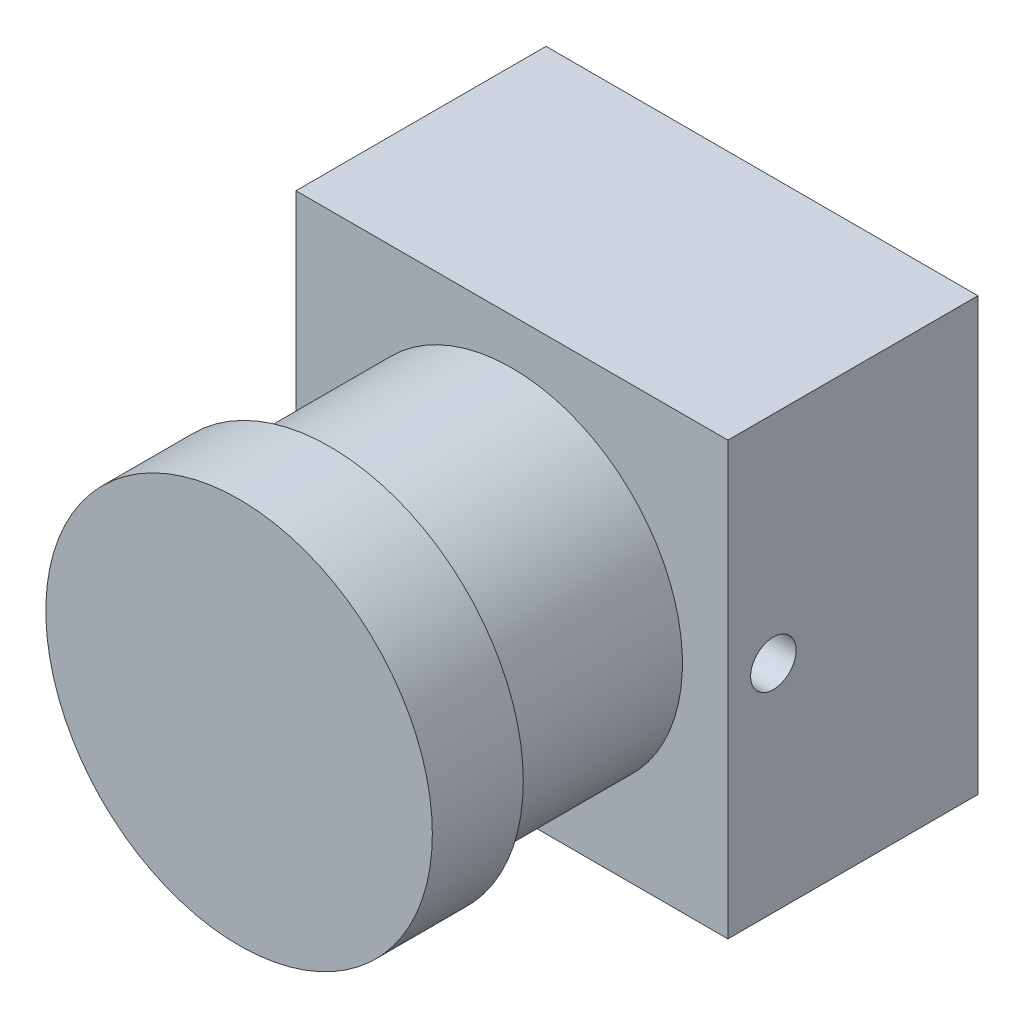
SolidWorks part; units mm, degrees
ref_plane "Front Plane" through (0, 0, 0) normal (0, 0, 1) x (1, 0, 0)
ref_plane "Top Plane" through (0, 0, 0) normal (0, 1, 0) x (1, 0, 0)
ref_plane "Right Plane" through (0, 0, 0) normal (1, 0, 0) x (0, 0, -1)
sketch "Sketch1" plane through (0, 0, 0) normal (0, 0, 1) x (1, 0, 0)
  line L1 (0, 0) -> (19, 0)
  line L2 (0, 0) -> (0, 19)
  line L3 (0, 19) -> (19, 19)
  line L4 (19, 0) -> (19, 19)
  dimension "D1" = 19
extrude "Boss-Extrude1" add sketch "Sketch1" along normal blind 11
sketch "Sketch2" plane through (0, 0, 11) normal (0, 0, 1) x (1, 0, 0)
  line L0 (0, 19) -> (19, 0) construction
  line L1 (19, 19) -> (0, 0) construction
  circle A0 centre (9.5, 9.5) radius 7.5
  point P11 (9.5, 9.5)
  dimension "D1" = 15
extrude "Boss-Extrude2" add sketch "Sketch2" along normal blind 8
sketch "Sketch4" plane through (0, 0, 19) normal (0, 0, 1) x (1, 0, 0)
  circle A0 centre (9.5, 9.5) radius 8.5
  circle A1 centre (9.5, 9.5) radius 7.5 construction
  dimension "D1" = 17
extrude "Boss-Extrude3" add sketch "Sketch4" along normal blind 4
sketch "Sketch3" plane through (19, 0, 0) normal (1, 0, 0) x (0, 0, -1)
  line L0 (-11, 9.5) -> (0, 9.5) construction
  line L1 (-11, 0) -> (-11, 19) construction
  line L2 (0, 0) -> (0, 19) construction
  circle A0 centre (-9, 9.5) radius 1
  dimension "D1" = 9
  dimension "D2" = 2
extrude "Cut-Extrude1" cut sketch "Sketch3" against normal through all
ref_plane "Plane1" through (9.5, 0, 0) normal (1, 0, 0) x (0, 0, -1)
